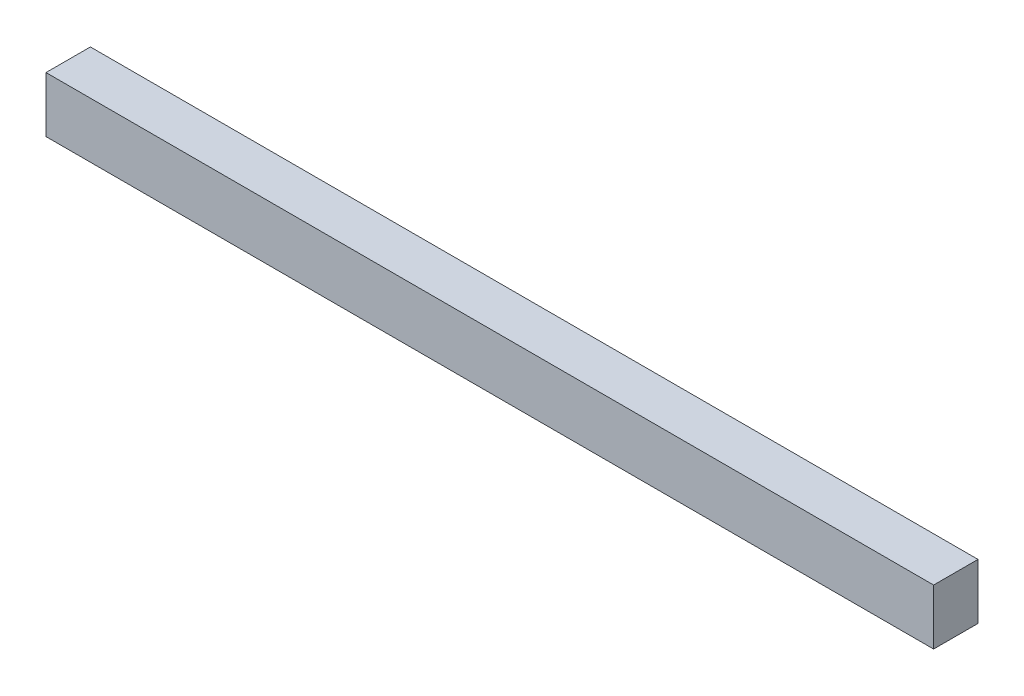
SolidWorks part; units mm, degrees
material "Oak"
ref_plane "Front Plane" through (0, 0, 0) normal (0, 0, 1) x (1, 0, 0)
ref_plane "Top Plane" through (0, 0, 0) normal (0, 1, 0) x (1, 0, 0)
ref_plane "Right Plane" through (0, 0, 0) normal (1, 0, 0) x (0, 0, -1)
sketch "Sketch1" plane through (0, 0, 0) normal (0, 1, 0) x (1, 0, 0)
  line L1 (400, -20) -> (-400, -20)
  line L2 (400, -20) -> (400, 20)
  line L3 (400, 20) -> (-400, 20)
  line L4 (-400, -20) -> (-400, 20)
  line L5 (400, -20) -> (-400, 20) construction
  line L6 (400, 20) -> (-400, -20) construction
  point P0 (0, 0)
  dimension "D1" = 800
  dimension "D2" = 40
extrude "Boss-Extrude1" add sketch "Sketch1" along normal blind 50
